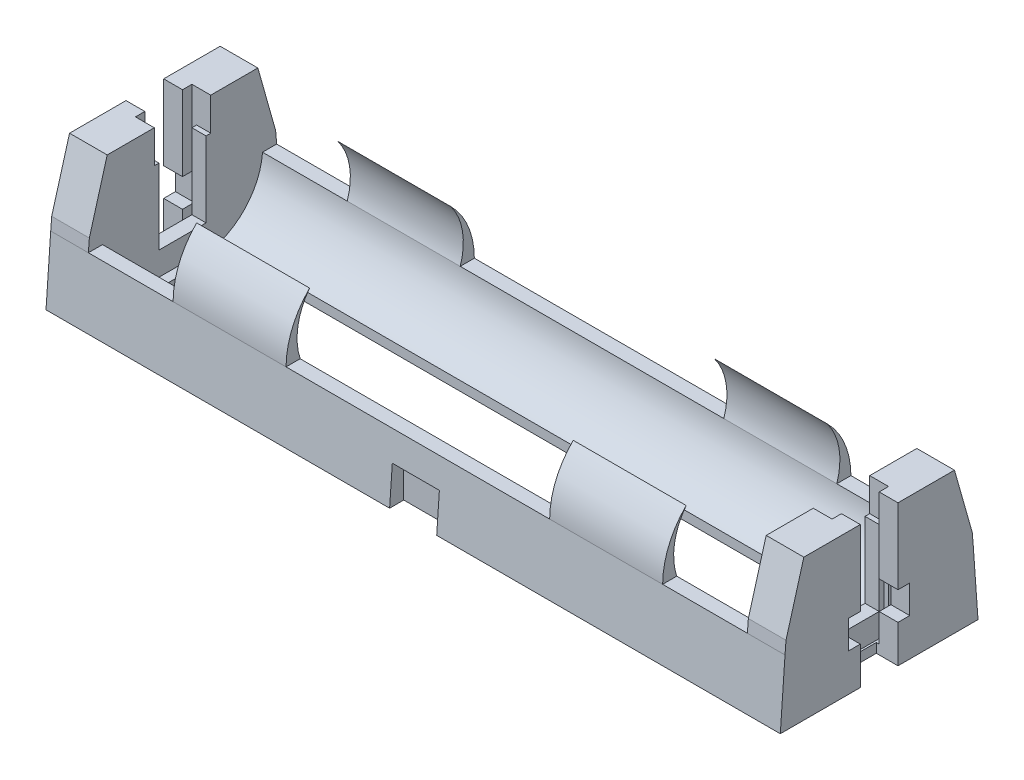
SolidWorks part; units mm, degrees
ref_plane "Front Plane" through (0, 0, 0) normal (0, 0, 1) x (1, 0, 0)
ref_plane "Top Plane" through (0, 0, 0) normal (0, 1, 0) x (1, 0, 0)
ref_plane "Right Plane" through (0, 0, 0) normal (1, 0, 0) x (0, 0, -1)
sketch "Sketch1" plane through (0, 0, 0) normal (0, 1, 0) x (1, 0, 0)
  line L0 (0, 10.5) -> (0, -10.5) construction
  line L1 (-39, 0) -> (39, 0) construction
  line L2 (-39, 10.5) -> (-39, -10.5)
  line L3 (-39, -10.5) -> (39, -10.5)
  line L4 (39, -10.5) -> (39, 10.5)
  line L5 (39, 10.5) -> (-39, 10.5)
  point P4 (0, 0)
  point P8 (0, 0)
  dimension "D1" = 21
  dimension "D2" = 78
extrude "Boss-Extrude1" add sketch "Sketch1" along normal blind 7
sketch "Sketch2" plane through (39, 0, 0) normal (1, 0, 0) x (0, 0, -1)
  line L0 (-10, 7) -> (10, 7) construction
  line L1 (-10.5, 7) -> (10.5, 7) construction
  line L3 (10, 7) -> (10.5, 0)
  line L4 (10.5, 0) -> (10.5, 7)
  line L5 (10.5, 7) -> (10, 7)
  line L6 (-10, 7) -> (-10.5, 0)
  line L7 (-10.5, 0) -> (-10.5, 7)
  line L8 (-10.5, 7) -> (-10, 7)
  point P5 (0, 7)
  dimension "D1" = 20
  dimension "D2" = 10.5
extrude "Cut-Extrude1" cut sketch "Sketch2" against normal through all
sketch "Sketch3" plane through (0, 7, 0) normal (0, 1, 0) x (1, 0, 0)
  line L0 (-35, 0) -> (35, 0) construction
  line L1 (0, 4) -> (0, -4) construction
  line L2 (-35, 4) -> (-35, -4)
  line L3 (-35, -4) -> (35, -4)
  line L4 (35, -4) -> (35, 4)
  line L5 (35, 4) -> (-35, 4)
  point P4 (0, 0)
  point P8 (0, 0)
  dimension "D1" = 70
  dimension "D2" = 8
extrude "Cut-Extrude2" cut sketch "Sketch3" against normal blind 6
ref_plane "Plane1" through (35, 0, 0) normal (1, 0, 0) x (0, 0, -1)
sketch "Sketch4" plane through (35, 0, 0) normal (1, 0, 0) x (0, 0, -1)
  line L0 (-10, 7) -> (10, 7) construction
  line L1 (-10.5, 0) -> (10.5, 0) construction
  line L2 (-13.5905, 3.5) -> (13.5905, 3.5) construction
  line L3 (7.25, 8.4027) -> (7.25, -1.4027) construction
  line L4 (4, 1) -> (4, 7)
  line L5 (4, 7) -> (8.5, 7)
  arc A0 (8.5, 7) -> (4, 1) centre (1.5909, 7.4943) cw
  point P0 (8.5, 7)
  point P1 (4, 1)
  point P10 (0, 3.5)
  point P13 (7.25, 3.5)
  dimension "D1" = 1.5
  dimension "D2" = 1
  dimension "D3" = 3.5
  dimension "D4" = 6.5
  dimension "D5" = 3.25
  dimension "D6" = 10.5
extrude "Cut-Extrude3" cut sketch "Sketch4" against normal blind 70
mirror "Mirror1" about plane through (0, 0, 0) normal (0, 0, 1) of "Cut-Extrude3"
sketch "Sketch5" plane through (0, 1, 0) normal (0, 1, 0) x (1, 0, 0)
  line L0 (-34, 4) -> (34, 4)
  line L1 (35, 4) -> (-35, 4) construction
  line L2 (34, 4) -> (34, -4)
  line L3 (-35, -4) -> (35, -4) construction
  line L4 (34, -4) -> (-34, -4)
  line L5 (-34, -4) -> (-34, 4)
  line L6 (-35, 4) -> (-35, -4) construction
  line L7 (35, -8.5) -> (35, 8.5) construction
  dimension "D1" = 1
  dimension "D2" = 1
extrude "Cut-Extrude4" cut sketch "Sketch5" against normal through all
ref_plane "Plane2" through (26, 0, 0) normal (1, 0, 0) x (0, 0, -1)
sketch "Sketch6" plane through (26, 0, 0) normal (1, 0, 0) x (0, 0, -1)
  line L0 (-10, 7) -> (-8.5, 7)
  line L1 (-10, 7) -> (10, 7) construction
  arc A0 (-7.5, 13) -> (-10, 7) centre (-1.4706, 6.9669) ccw
  arc A1 (-7.5, 13) -> (-8.5, 7) centre (-2.2973, 9.0495) ccw
  point P5 (-7.5, 13)
  dimension "D1" = 1.5
  dimension "D2" = 6
  dimension "D3" = 2.5
extrude "Boss-Extrude2" add sketch "Sketch6" against normal blind 12
mirror "Mirror2" about plane through (0, 0, 0) normal (1, 0, 0) of "Boss-Extrude2"
mirror "Mirror3" about plane through (0, 0, 0) normal (0, 0, 1) of "Mirror2", "Boss-Extrude2"
sketch "Sketch8" plane through (39, 0, 0) normal (1, 0, 0) x (0, 0, -1)
  line L0 (-8, 15) -> (8, 15)
  line L1 (-8, 15) -> (-9.8946, 8.3043)
  line L2 (-9.8946, 8.3043) -> (-10, 7)
  line L3 (-10, 7) -> (10, 7)
  line L4 (10, 7) -> (9.8946, 8.3043)
  line L5 (9.8946, 8.3043) -> (8, 15)
  arc A0 (-7.5, 13) -> (-10, 7) centre (-1.4706, 6.9669) ccw construction
  arc A1 (10, 7) -> (7.5, 13) centre (1.4706, 6.9669) ccw construction
  point P3 (0, 15)
  dimension "D1" = 16
  dimension "D2" = 0
  dimension "D3" = 1.3043
  dimension "D4" = 8
  dimension "D5" = 1.3043
extrude "Boss-Extrude3" add sketch "Sketch8" against normal blind 4
mirror "Mirror4" about plane through (0, 0, 0) normal (1, 0, 0) of "Boss-Extrude3"
sketch "Sketch9" plane through (39, 0, 0) normal (1, 0, 0) x (0, 0, -1)
  line L0 (-12.9354, 5.5) -> (12.9354, 5.5) construction
  line L1 (-10.5, 0) -> (10.5, 0) construction
  line L2 (-3.25, 7) -> (3.25, 7)
  line L3 (-3.25, 7) -> (-3.25, 4)
  line L4 (-3.25, 4) -> (3.25, 4)
  line L5 (3.25, 4) -> (3.25, 7)
  point P3 (0, 5.5)
  point P5 (0, 0)
  dimension "D1" = 5.5
  dimension "D2" = 6.5
  dimension "D3" = 1.5
  dimension "D4" = 3
  dimension "D5" = 3.25
extrude "Cut-Extrude5" cut sketch "Sketch9" against normal blind 2
mirror "Mirror5" about plane through (0, 0, 0) normal (1, 0, 0) of "Cut-Extrude5"
sketch "Sketch11" plane through (35, 0, 0) normal (-1, 0, 0) x (0, 0, 1)
  line L0 (-2.5, 3.5) -> (2.5, 3.5)
  line L1 (-8, 15) -> (8, 15) construction
  line L2 (2.5, 3.5) -> (2.5, 11.5)
  line L3 (0, 16.4586) -> (0, -3.6324) construction
  line L4 (2.5, 11.5) -> (3, 11.5)
  line L5 (3, 11.5) -> (3, 15)
  line L6 (-2.5, 3.5) -> (-2.5, 11.5)
  line L7 (-2.5, 11.5) -> (-3, 11.5)
  line L8 (-3, 11.5) -> (-3, 15)
  line L9 (-3, 15) -> (3, 15)
  point P3 (0, 3.5)
  dimension "D1" = 11.5
  dimension "D2" = 5
  dimension "D3" = 0.5
  dimension "D4" = 3.5
extrude "Cut-Extrude6" cut sketch "Sketch11" against normal blind 2
sketch "Sketch12" plane through (0, 11.5, 0) normal (0, 1, 0) x (1, 0, 0)
  line L0 (37, 3) -> (37, -3)
  line L1 (37, -3) -> (36.5, -3)
  line L2 (37, -3) -> (35, -3) construction
  line L3 (36.5, -3) -> (36.5, 3)
  line L4 (37, 3) -> (35, 3) construction
  line L5 (36.5, 3) -> (37, 3)
  dimension "D1" = 0.5
extrude "Cut-Extrude8" cut sketch "Sketch12" against normal blind 10.5 contours L3 L5 L0 L1
sketch "Sketch13" plane through (39, 0, 0) normal (1, 0, 0) x (0, 0, -1)
  line L0 (-2.0009, 15) -> (2.0009, 15)
  line L1 (8, 15) -> (-8, 15) construction
  line L2 (2.0009, 15) -> (2.0009, 0)
  line L3 (-10.5, 0) -> (10.5, 0) construction
  line L4 (2.0009, 0) -> (-2.0009, 0)
  line L5 (-2.0009, 0) -> (-2.0009, 15)
  point P5 (0, 15)
  dimension "D1" = 4.0019
extrude "Cut-Extrude9" cut sketch "Sketch13" against normal blind 2.3
mirror "Mirror6" about plane through (0, 0, 0) normal (1, 0, 0) of "Cut-Extrude6", "Cut-Extrude8", "Cut-Extrude9"
sketch "Sketch14" plane through (0, 0, 0) normal (0, -1, 0) x (1, 0, 0)
  line L0 (0, 17.236) -> (0, -18.0266) construction
  line L1 (-2.5, 10.5) -> (2.5, 10.5)
  line L2 (-39, 10.5) -> (39, 10.5) construction
  line L3 (-2.5, 10.5) -> (-2.5, 9)
  line L4 (-2.5, 9) -> (2.5, 9)
  line L5 (2.5, 9) -> (2.5, 10.5)
  point P8 (0, 10.5)
  dimension "D1" = 5
  dimension "D2" = 2.5
  dimension "D3" = 1.5
extrude "Cut-Extrude10" cut sketch "Sketch14" against normal blind 4
mirror "Mirror7" about plane through (0, 0, 0) normal (0, 0, 1) of "Cut-Extrude10"
